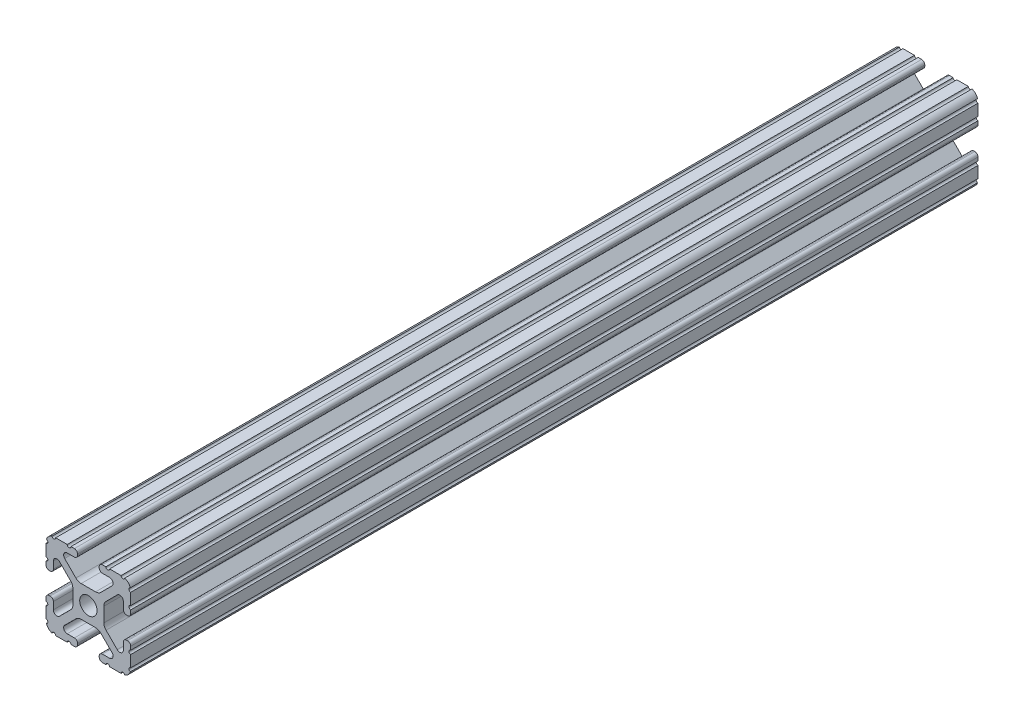
SolidWorks part; units mm, degrees
material "6061 Alloy"
ref_plane "Front Plane" through (0, 0, 0) normal (0, 0, 1) x (1, 0, 0)
ref_plane "Top Plane" through (0, 0, 0) normal (0, 1, 0) x (1, 0, 0)
ref_plane "Right Plane" through (0, 0, 0) normal (1, 0, 0) x (0, 0, -1)
sketch "Sketch2" plane through (0, 0, 0) normal (0, 0, 1) x (1, 0, 0)
  line L0 (0, 12.7) -> (0, -12.7) construction
  line L1 (-12.7, 0) -> (12.7, 0) construction
  line L2 (3.2512, -12.7) -> (12.7, -12.7)
  line L3 (12.7, -12.7) -> (12.7, -3.2512)
  line L4 (3.2512, -12.7) -> (3.2512, -10.4902)
  line L5 (3.2512, -10.4902) -> (8.9276, -10.4902)
  line L6 (8.9276, -10.4902) -> (3.0856, -4.6482)
  line L7 (0, 0) -> (12.7, -12.7) construction
  line L8 (12.7, -3.2512) -> (10.4902, -3.2512)
  line L9 (10.4902, -3.2512) -> (10.4902, -8.9276)
  line L10 (10.4902, -8.9276) -> (4.6482, -3.0856)
  circle A0 centre (0, 0) radius 2.6035
  arc A1 (6.3485, -10.4902) -> (7.1039, -8.6665) centre (6.3485, -9.4219) ccw construction
  point P8 (0, -4.6482)
  dimension "Center Hole Diameter" = 5.207
  dimension "Rail Height" = 25.4
  dimension "Rail Width" = 25.4
  dimension "T-Slot Width" = 6.5024
  dimension "Slot Inner Width" = 14.8336
  dimension "Thickness" = 2.2098
  dimension "Slot Depth" = 5.842
  dimension "D1" = 2.2098
sketch "Sketch3" plane through (0, 0, 0) normal (1, 0, 0) x (0, 0, -1)
  line L0 (-127, -12.7) -> (127, -12.7) construction
  line L1 (-96.52, 0) -> (96.52, 0) construction
  dimension "Length" = 254
  dimension "D1" = 30.48
sketch "Sketch4" plane through (0, 0, 0) normal (0, 0, 1) x (1, 0, 0)
  line L0 (4.1904, -12.7) -> (10.1173, -12.7)
  line L1 (3.2512, -12.7) -> (12.7, -12.7) construction
  line L2 (3.2512, -12.7) -> (3.2512, -10.4902) construction
  line L3 (3.2512, -10.4902) -> (8.9276, -10.4902) construction
  line L4 (3.2512, -11.4294) -> (3.2512, -11.7608)
  line L5 (4.1904, -10.4902) -> (6.3485, -10.4902)
  line L6 (0, -4.6482) -> (2.164, -4.6482)
  line L7 (8.9276, -10.4902) -> (3.0856, -4.6482) construction
  line L8 (3.7373, -5.2999) -> (7.1039, -8.6665)
  line L9 (12.7, -12.7) -> (12.7, -3.2512) construction
  line L10 (10.4902, -8.9276) -> (4.6482, -3.0856) construction
  line L11 (10.4902, -3.2512) -> (10.4902, -8.9276) construction
  line L12 (10.4902, -6.3485) -> (10.4902, -4.1904)
  line L13 (12.7, -3.2512) -> (10.4902, -3.2512) construction
  line L14 (11.4294, -3.2512) -> (11.7608, -3.2512)
  line L15 (12.7, -4.1904) -> (12.7, -10.1173)
  line L16 (8.6665, -7.1039) -> (5.2999, -3.7373)
  line L17 (4.6482, 0) -> (4.6482, -2.164)
  line L18 (-12.7, 0) -> (12.7, 0) construction
  line L19 (0, -4.6482) -> (0, -2.6035)
  line L20 (0, 12.7) -> (0, -12.7) construction
  line L21 (4.6482, 0) -> (2.6035, 0)
  arc A0 (3.2512, -11.7608) -> (4.1904, -12.7) centre (4.1904, -11.7608) ccw
  arc A2 (3.2512, -11.4294) -> (4.1904, -10.4902) centre (4.1904, -11.4294) cw
  arc A3 (6.3485, -10.4902) -> (7.1039, -8.6665) centre (6.3485, -9.4219) ccw
  arc A4 (2.164, -4.6482) -> (3.7373, -5.2999) centre (2.164, -6.8732) cw
  arc A5 (10.1173, -12.7) -> (12.7, -10.1173) centre (10.1173, -10.1173) ccw
  arc A6 (8.6665, -7.1039) -> (10.4902, -6.3485) centre (9.4219, -6.3485) ccw
  arc A7 (10.4902, -4.1904) -> (11.4294, -3.2512) centre (11.4294, -4.1904) cw
  arc A8 (11.7608, -3.2512) -> (12.7, -4.1904) centre (11.7608, -4.1904) cw
  arc A9 (5.2999, -3.7373) -> (4.6482, -2.164) centre (6.8732, -2.164) cw
  circle A10 centre (0, 0) radius 2.6035 construction
  arc A11 (0, -2.6035) -> (2.6035, 0) centre (0, 0) ccw
  dimension "D1" = 2.5827
  dimension "D2" = 2.225
  dimension "D3" = 0.9392
extrude "Boss-Extrude1" add sketch "Sketch4" along normal mid plane 254
sketch "Sketch5" plane through (0, 0, 0) normal (0, 0, 1) x (1, 0, 0)
  line L0 (3.2512, -12.7) -> (12.7, -12.7) construction
  line L1 (4.1904, -10.4902) -> (6.3485, -10.4902) construction
  line L3 (0, 0) -> (12.7, -12.7) construction
  line L4 (6.3485, -10.4902) -> (6.3485, -12.7) construction
  line L5 (8.9276, -10.4902) -> (3.0856, -4.6482) construction
  circle A0 centre (10.3562, -12.7) radius 0.5524
  circle A1 centre (5.796, -12.7) radius 0.5524
  circle A2 centre (12.7, -10.3562) radius 0.5524
  circle A3 centre (12.7, -5.796) radius 0.5524
  point P10 (5.2694, -10.4902)
  point P12 (9.4219, -6.3485)
  dimension "D1" = 1.1049
extrude "Cut-Extrude1" cut sketch "Sketch5" against normal through all both and the other way through all
mirror "Mirror1" about plane through (0, 0, 0) normal (1, 0, 0) of bodies 137 134
mirror "Mirror2" about plane through (0, 0, 0) normal (0, 1, 0) of bodies 135
equation "\"D1@Boss-Extrude1\"=\"Length@Sketch3\""
equation "\"D1@Sketch2\"=\"Thickness@Sketch2\""
equation "\"D2@Sketch4\"=\"Slot Inner Width@Sketch2\"*0.15"
equation "\"D1@Sketch4\"=\"D3@Sketch4\"*2.75"
equation "\"D3@Sketch4\"=\"Thickness@Sketch2\"*0.425"
equation "\"D1@Sketch5\"=\"Thickness@Sketch2\"*0.5"
